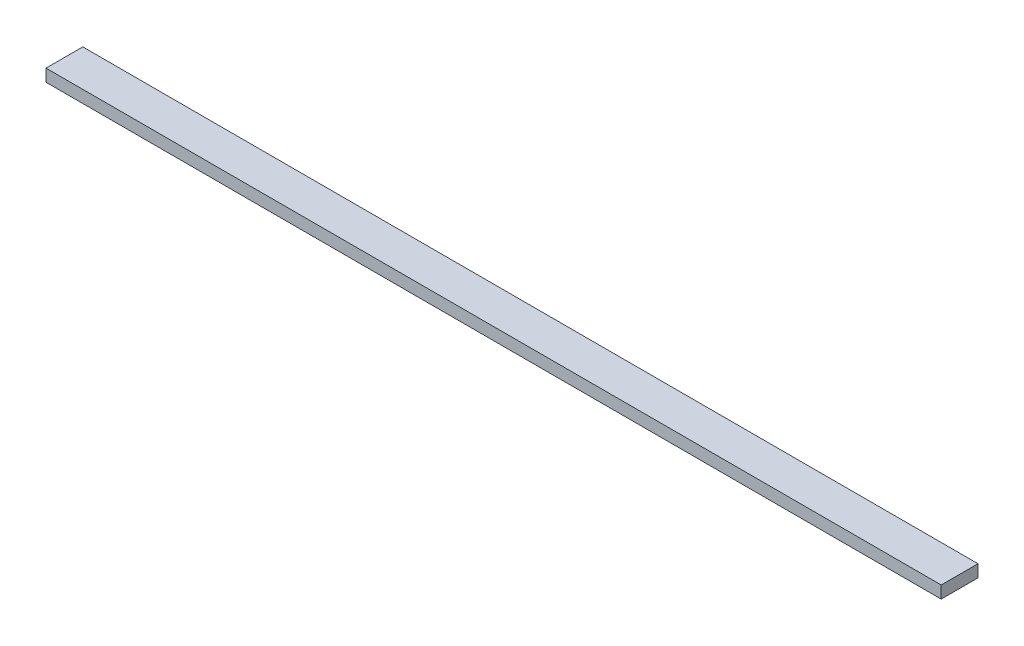
SolidWorks part; units mm, degrees
ref_plane "Front Plane" through (0, 0, 0) normal (0, 0, 1) x (1, 0, 0)
ref_plane "Top Plane" through (0, 0, 0) normal (0, 1, 0) x (1, 0, 0)
ref_plane "Right Plane" through (0, 0, 0) normal (1, 0, 0) x (0, 0, -1)
sketch "Sketch1" plane through (0, 0, 0) normal (0, 1, 0) x (1, 0, 0)
  line L1 (0, 0) -> (927.1, 0)
  line L2 (0, 0) -> (0, 38.1)
  line L3 (0, 38.1) -> (927.1, 38.1)
  line L4 (927.1, 0) -> (927.1, 38.1)
  dimension "D1" = 927.1
  dimension "D2" = 38.1
extrude "Boss-Extrude1" add sketch "Sketch1" along normal blind 12.7
